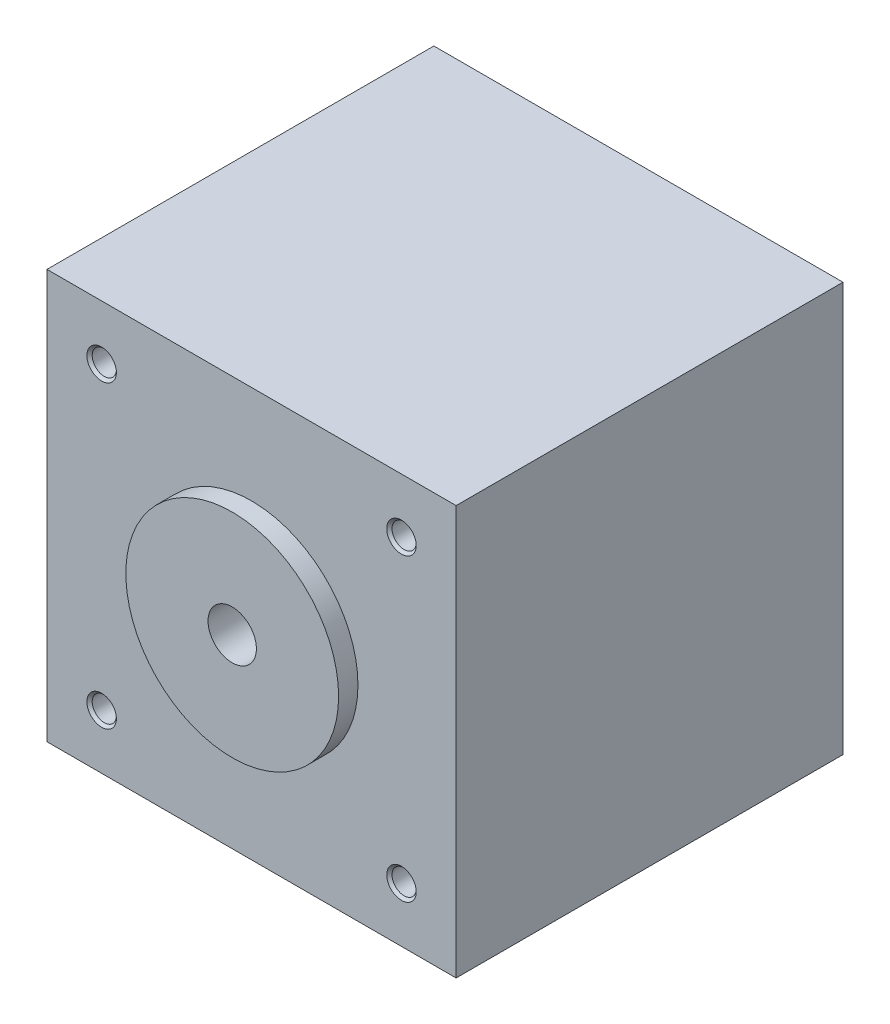
SolidWorks part; units mm, degrees
ref_plane "정면" through (0, 0, 0) normal (0, 0, 1) x (1, 0, 0)
ref_plane "윗면" through (0, 0, 0) normal (0, 1, 0) x (1, 0, 0)
ref_plane "우측면" through (0, 0, 0) normal (1, 0, 0) x (0, 0, -1)
sketch "스케치1" plane through (0, 0, 0) normal (0, 0, 1) x (1, 0, 0)
  line L1 (-21.15, 21.15) -> (21.15, 21.15)
  line L2 (-21.15, 21.15) -> (-21.15, -21.15)
  line L3 (-21.15, -21.15) -> (21.15, -21.15)
  line L4 (21.15, 21.15) -> (21.15, -21.15)
  line L5 (-21.15, 21.15) -> (21.15, -21.15) construction
  line L6 (-21.15, -21.15) -> (21.15, 21.15) construction
  point P0 (0, 0)
  dimension "D1" = 42.3
  dimension "D2" = 42.3
extrude "보스-돌출1" add sketch "스케치1" along normal blind 40
hole_wizard "M3 나사 구멍1" positions "스케치3" profile "스케치5" tap size "M3" standard "KS"
sketch "스케치3" plane through (0, 0, 40) normal (0, 0, 1) x (1, 0, 0)
  line L1 (-21.15, 21.15) -> (-21.15, -21.15) construction
  line L2 (21.15, 21.15) -> (-21.15, 21.15) construction
  point P0 (-15.5, 15.5)
  point P2 (15.5, 15.5)
  point P4 (15.5, -15.5)
  point P6 (-15.5, -15.5)
  point P11 (0, 0)
  point P12 (0, 0)
  point P13 (0, 0)
  point P14 (0, 0)
  point P15 (0, 0)
  point P16 (0, 0)
  dimension "D1" = 31
  dimension "D2" = 31
  dimension "D3" = 5.65
  dimension "D4" = 5.65
sketch "스케치5" plane through (-15.5, 15.5, 40) normal (1, 0, 0) x (0, -1, 0)
  line L0 (0, 0) -> (0, 9.2511)
  line L1 (0, 9.2511) -> (1.25, 8.5)
  line L2 (1.25, 8.5) -> (1.25, 0.275)
  line L3 (1.25, 0.275) -> (1.525, 0)
  line L5 (1.525, 0) -> (0, 0)
  line L6 (-1.25, 0.275) -> (-1.525, 0) construction
  line L10 (0, 9.2511) -> (-1.25, 8.5) construction
  line L11 (0, -6.35) -> (0, 107.95) construction
  dimension "탭 드릴 지름" = 2.5
  dimension "탭 드릴 깊이" = 8.5
  dimension "표면 카운터싱크 지름" = 3.05
  dimension "표면 카운터싱크 각도" = 90
  dimension "드릴 각도" = 118
cosmetic thread "구멍 나사산1" parameters "D1"=6, "D2"=3
cosmetic thread "구멍 나사산2" parameters "D1"=6, "D2"=3
cosmetic thread "구멍 나사산3" parameters "D1"=6, "D2"=3
cosmetic thread "구멍 나사산4" parameters "D1"=6, "D2"=3
sketch "스케치6" plane through (0, 0, 40) normal (0, 0, 1) x (1, 0, 0)
  circle A0 centre (0, 0) radius 11
  dimension "D1" = 22
extrude "보스-돌출2" add sketch "스케치6" along normal blind 2
ref_plane "평면1" through (0, 0, 20) normal (0, 0, -1) x (-1, 0, 0)
mirror "대칭 복사1" about plane through (0, 0, 20) normal (0, 0, -1) of "보스-돌출2"
sketch "스케치7" plane through (0, 0, 42) normal (0, 0, 1) x (1, 0, 0)
  circle A0 centre (0, 0) radius 2.5
  dimension "D1" = 5
extrude "컷-돌출1" cut sketch "스케치7" against normal through all
